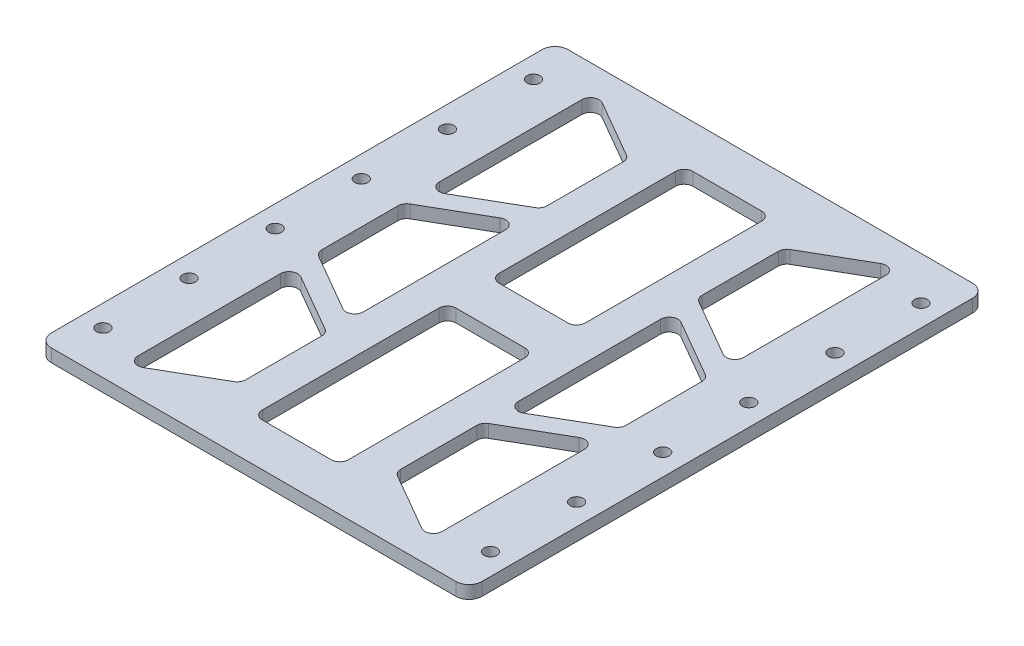
SolidWorks part; units mm, degrees
material "Thornel Mat VMA"
ref_plane "前视基准面" through (0, 0, 0) normal (0, 0, 1) x (1, 0, 0)
ref_plane "上视基准面" through (0, 0, 0) normal (0, 1, 0) x (1, 0, 0)
ref_plane "右视基准面" through (0, 0, 0) normal (1, 0, 0) x (0, 0, -1)
other "Configuration Table"
sketch "草图1" plane through (0, 0, 0) normal (0, 1, 0) x (1, 0, 0)
  line L0 (0, 0) -> (0, 74.7884) construction
  line L1 (-50, -60) -> (50, -60)
  line L2 (-50, -60) -> (-50, 60)
  line L3 (-50, 60) -> (50, 60)
  line L4 (50, -60) -> (50, 60)
  line L5 (-50, -60) -> (50, 60) construction
  line L6 (-50, 60) -> (50, -60) construction
  line L7 (0, 0) -> (70.8425, 0) construction
  line L11 (-35.3205, 55) -> (-35.3205, 15)
  line L12 (-35.3205, 15) -> (-18, 25)
  line L13 (-18, 25) -> (-18, 45)
  line L14 (-18, 45) -> (-35.3205, 55)
  line L15 (-35.3205, 10) -> (-35.3205, -10)
  line L16 (-35.3205, -10) -> (-18, -20)
  line L17 (-18, -20) -> (-18, 20)
  line L18 (-18, 20) -> (-35.3205, 10)
  line L19 (-18, -25) -> (-18, -45)
  line L20 (-35.3205, -15) -> (-18, -25)
  line L21 (-35.3205, -55) -> (-35.3205, -15)
  line L22 (-18, -45) -> (-35.3205, -55)
  line L23 (35.3205, -15) -> (18, -25)
  line L24 (35.3205, -55) -> (35.3205, -15)
  line L25 (18, -45) -> (35.3205, -55)
  line L26 (18, -25) -> (18, -45)
  line L27 (18, -20) -> (18, 20)
  line L28 (35.3205, -10) -> (18, -20)
  line L29 (35.3205, 10) -> (35.3205, -10)
  line L30 (18, 20) -> (35.3205, 10)
  line L31 (18, 25) -> (18, 45)
  line L32 (35.3205, 15) -> (18, 25)
  line L33 (35.3205, 55) -> (35.3205, 15)
  line L34 (18, 45) -> (35.3205, 55)
  line L35 (-10, 5) -> (10, 5)
  line L36 (-10, -50) -> (10, -50)
  line L37 (-10, -50) -> (-10, 50)
  line L38 (-10, 50) -> (10, 50)
  line L39 (10, -50) -> (10, 50)
  line L40 (-10, -50) -> (10, 50) construction
  line L41 (-10, 50) -> (10, -50) construction
  line L42 (-10, -5) -> (10, -5)
  circle A0 centre (-45, 50) radius 1.5
  circle A1 centre (-45, 30) radius 1.5
  circle A2 centre (-45, 10) radius 1.5
  circle A3 centre (-45, -10) radius 1.5
  circle A4 centre (-45, -30) radius 1.5
  circle A5 centre (-45, -50) radius 1.5
  circle A6 centre (45, -50) radius 1.5
  circle A7 centre (45, -30) radius 1.5
  circle A8 centre (45, -10) radius 1.5
  circle A9 centre (45, 10) radius 1.5
  circle A10 centre (45, 30) radius 1.5
  circle A11 centre (45, 50) radius 1.5
  point P0 (0, 0)
  dimension "D3" = 3
  dimension "D7" = 20
  dimension "D1" = 100
  dimension "D2" = 120
  dimension "D4" = 45
  dimension "D5" = 50
  dimension "D8" = 40
  dimension "D9" = 20
  dimension "D10" = 20
  dimension "D11" = 20
  dimension "D12" = 18
  dimension "D13" = 25
  dimension "D14" = 40
  dimension "D15" = 20
  dimension "D16" = 20
  dimension "D17" = 10
  dimension "D18" = 20
  dimension "D19" = 100
  dimension "D20" = 5
  dimension "D6" = 6
extrude "凸台-拉伸1" add sketch "草图1" along normal blind 3 contours L1 L4 L3 L2 A10 A8 A6 A5 A4 A3 A2 A1 A0 L39 L36 L37 L38 L26 L23 L24 L25 L18 L17 L16 L15 L14 L13 L12 L11 L19 L22 L21 L20 | L37 L42 L39 L35
fillet "圆角1" radius 3 4 edges at (50, 1.5, -60) (-50, 1.5, -60) (50, 1.5, 60) (-50, 1.5, 60)
fillet "圆角2" radius 2 32 edges at (18, 1.5, -25) (18, 1.5, -45) (35.3205, 1.5, -55) (35.3205, 1.5, -15) (35.3205, 1.5, 10) (35.3205, 1.5, -10) (18, 1.5, 20) (18, 1.5, -20) (35.3205, 1.5, 15) (35.3205, 1.5, 55) (18, 1.5, 45) (18, 1.5, 25) (10, 1.5, 50) (10, 1.5, 5) (-10, 1.5, 5) (-10, 1.5, 50) (-18, 1.5, 45) (-35.3205, 1.5, 55) (-18, 1.5, 25) (-35.3205, 1.5, 15) (-18, 1.5, 20) (-35.3205, 1.5, 10) (-35.3205, 1.5, -10) (-18, 1.5, -20) (10, 1.5, -5) (-10, 1.5, -5) (10, 1.5, -50) (-10, 1.5, -50) (-18, 1.5, -45) (-18, 1.5, -25) (-35.3205, 1.5, -15) (-35.3205, 1.5, -55)
